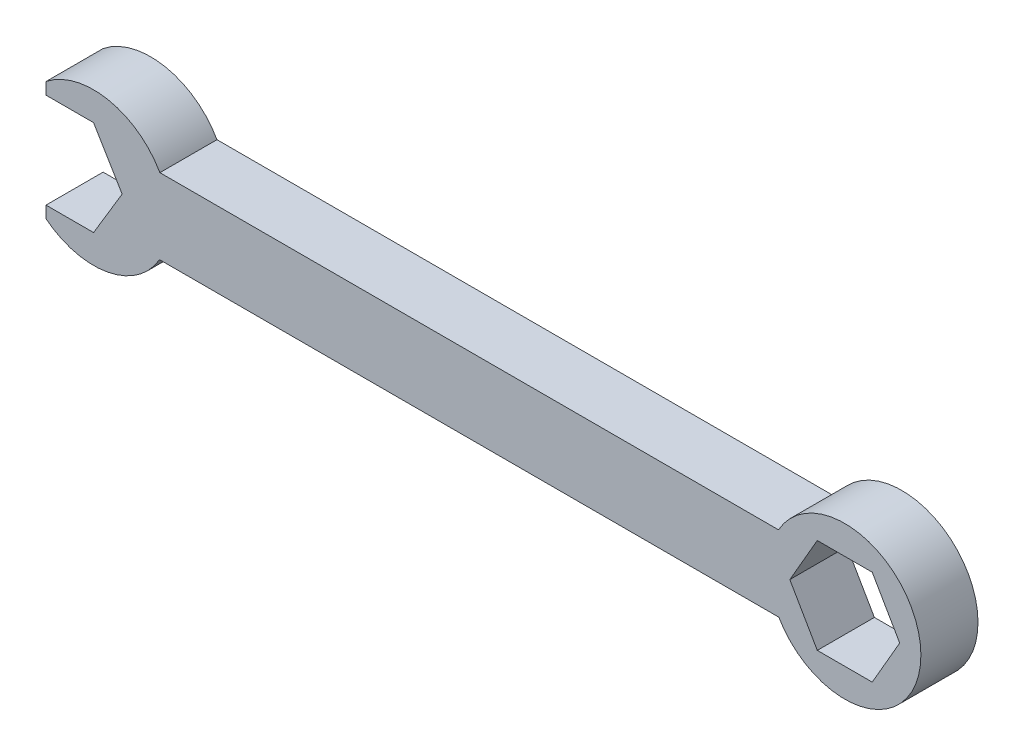
SolidWorks part; units mm, degrees
ref_plane "Front Plane" through (0, 0, 0) normal (0, 0, 1) x (1, 0, 0)
ref_plane "Top Plane" through (0, 0, 0) normal (0, 1, 0) x (1, 0, 0)
ref_plane "Right Plane" through (0, 0, 0) normal (1, 0, 0) x (0, 0, -1)
sketch "Sketch1" plane through (0, 0, 0) normal (0, 0, 1) x (1, 0, 0)
  line L0 (8.7988, -5.08) -> (91.4445, -5.08)
  line L1 (0, 6.35) -> (-6.35, 6.35)
  line L2 (-6.35, 6.35) -> (-6.35, 7.9311)
  line L3 (-6.35, 6.35) -> (0, 6.35)
  line L4 (3.81, 0) -> (110.4032, 0.0482)
  line L5 (0, 6.35) -> (3.81, 0)
  line L6 (3.81, 0) -> (0, -6.35)
  line L7 (0, -6.35) -> (-6.35, -6.35)
  line L8 (-6.35, -6.35) -> (-6.35, -7.9311)
  line L13 (107.5757, 0) -> (106.5933, 0)
  line L14 (96.5772, 6.35) -> (103.9095, 6.35)
  line L15 (107.5757, 0) -> (103.9095, 6.35)
  line L16 (103.9095, 6.35) -> (96.5772, 6.35)
  line L17 (96.5772, 6.35) -> (92.911, 0)
  line L18 (92.911, 0) -> (96.5772, -6.35)
  line L19 (96.5772, -6.35) -> (103.9095, -6.35)
  line L20 (103.9095, -6.35) -> (107.5757, 0)
  line L21 (96.5772, -6.35) -> (106.0444, -2.6522)
  line L22 (110.4032, 0.0482) -> (3.81, 0)
  line L24 (91.3967, 4.9962) -> (8.8467, 4.9962)
  line L29 (92.911, 0) -> (93.8933, 0)
  line L33 (102.7812, -5.08) -> (100.2433, -5.08)
  arc A0 (-6.35, -7.9311) -> (8.7988, -5.08) centre (0, 0) ccw
  circle A1 centre (100.2433, 0) radius 6.35 construction
  arc A2 (91.4445, -5.08) -> (91.3967, 4.9962) centre (100.2433, 0) ccw
  arc A3 (8.8467, 4.9962) -> (-6.35, 7.9311) centre (0, 0) ccw
  point P15 (7.9311, 0)
  dimension "D1" = 12.7
  dimension "D4" = 20.32
  dimension "D3" = 10.16
  dimension "D7" = 12.7
  dimension "D2" = 10.0762
  dimension "D5" = 6.35
  dimension "D6" = 10.16
  dimension "D8" = 82.55
extrude "Boss-Extrude2" add sketch "Sketch1" along normal blind 7.62 contours L24 A3 L2 L1 L5 L4 L17 L14 L15 A2 | L0 A2 L21 L20 L19 L18 L17 L4 L6 L7 L8 A0
